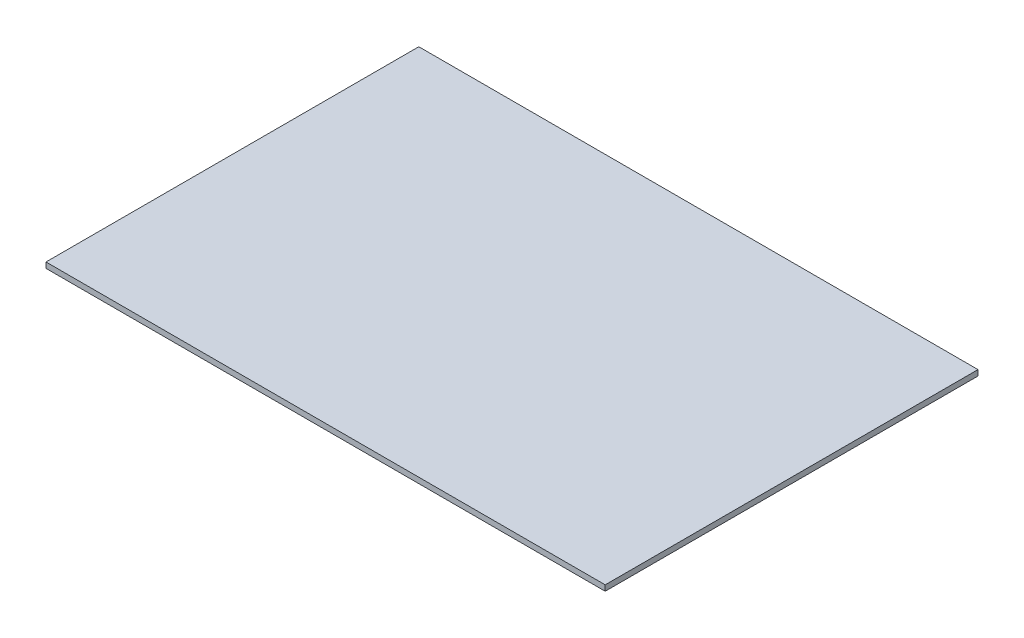
SolidWorks part; units mm, degrees
ref_plane "Front Plane" through (0, 0, 0) normal (0, 0, 1) x (1, 0, 0)
ref_plane "Top Plane" through (0, 0, 0) normal (0, 1, 0) x (1, 0, 0)
ref_plane "Right Plane" through (0, 0, 0) normal (1, 0, 0) x (0, 0, -1)
sketch "Sketch1" plane through (0, 0, 0) normal (0, 1, 0) x (1, 0, 0)
  line L1 (-150, -100) -> (150, -100)
  line L2 (-150, -100) -> (-150, 100)
  line L3 (-150, 100) -> (150, 100)
  line L4 (150, -100) -> (150, 100)
  line L5 (-150, -100) -> (150, 100) construction
  line L6 (-150, 100) -> (150, -100) construction
  point P0 (0, 0)
  dimension "D1" = 300
  dimension "D2" = 200
extrude "Boss-Extrude1" add sketch "Sketch1" along normal blind 3
